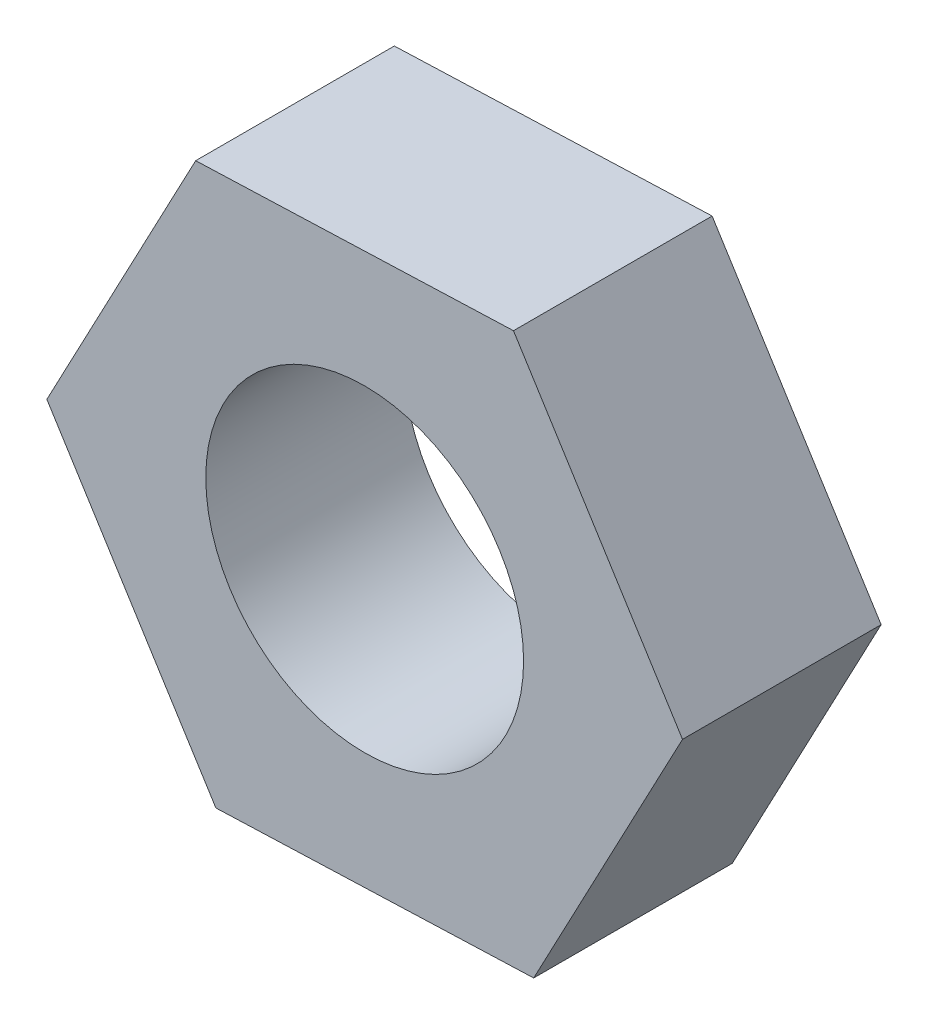
SolidWorks part; units mm, degrees
ref_plane "前视基准面" through (0, 0, 0) normal (0, 0, 1) x (1, 0, 0)
ref_plane "上视基准面" through (0, 0, 0) normal (0, 1, 0) x (1, 0, 0)
ref_plane "右视基准面" through (0, 0, 0) normal (1, 0, 0) x (0, 0, -1)
sketch "草图1" plane through (0, 0, 0) normal (0, 0, 1) x (1, 0, 0)
  line L1 (2.2474, 4.245) -> (-2.5526, 4.0688)
  line L2 (-2.5526, 4.0688) -> (-4.8, -0.1762)
  line L3 (-4.8, -0.1762) -> (-2.2474, -4.245)
  line L4 (-2.2474, -4.245) -> (2.5526, -4.0688)
  line L5 (2.5526, -4.0688) -> (4.8, 0.1762)
  line L6 (4.8, 0.1762) -> (2.2474, 4.245)
  circle A0 centre (0, 0) radius 4.1597 construction
  dimension "D1" = 4.8
extrude "凸台-拉伸1" add sketch "草图1" along normal blind 3
sketch "草图2" plane through (0, 0, 0) normal (0, 0, -1) x (-1, 0, 0)
  circle A0 centre (0, 0) radius 2.4
extrude "切除-拉伸1" cut sketch "草图2" against normal blind 3
